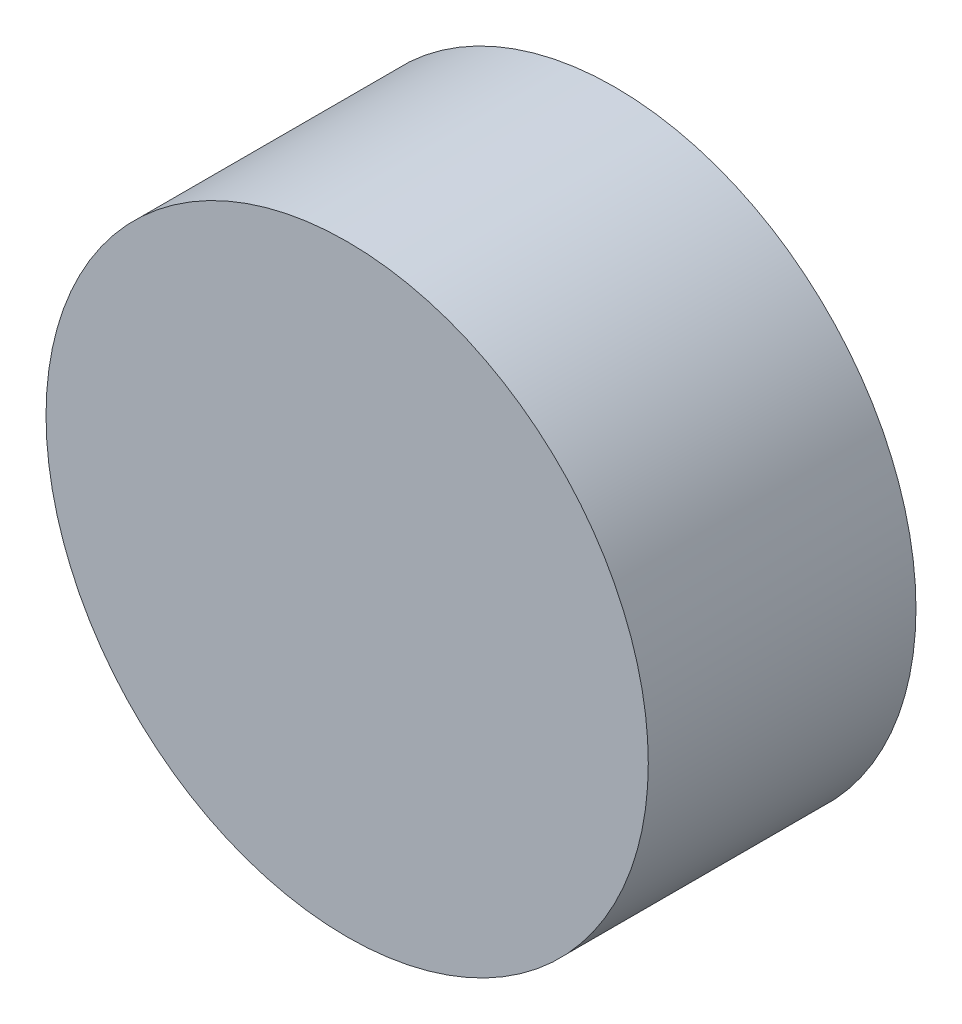
SolidWorks part; units mm, degrees
ref_plane "Front Plane" through (0, 0, 0) normal (0, 0, 1) x (1, 0, 0)
ref_plane "Top Plane" through (0, 0, 0) normal (0, 1, 0) x (1, 0, 0)
ref_plane "Right Plane" through (0, 0, 0) normal (1, 0, 0) x (0, 0, -1)
sketch "Sketch1" plane through (0, 0, 0) normal (0, 0, 1) x (1, 0, 0)
  circle A0 centre (0, 0) radius 45
  dimension "D1" = 90
extrude "Boss-Extrude1" add sketch "Sketch1" along normal blind 40
